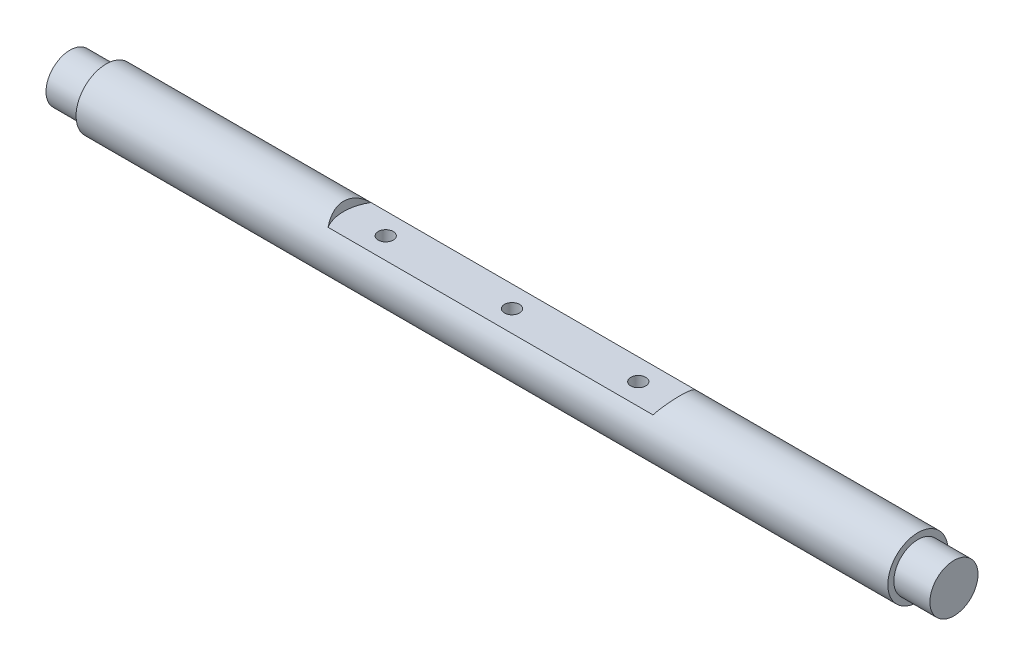
SolidWorks part; units mm, degrees
ref_plane "Plan de face" through (0, 0, 0) normal (0, 0, 1) x (1, 0, 0)
ref_plane "Plan de dessus" through (0, 0, 0) normal (0, 1, 0) x (1, 0, 0)
ref_plane "Plan de droite" through (0, 0, 0) normal (1, 0, 0) x (0, 0, -1)
sketch "Esquisse1" plane through (0, 0, 0) normal (0, 0, 1) x (1, 0, 0)
  line L0 (-67.5, 5) -> (67.5, 5)
  line L1 (67.5, 5) -> (67.5, 4)
  line L2 (67.5, 4) -> (73.5, 4)
  line L3 (73.5, 4) -> (73.5, 0)
  line L4 (73.5, 0) -> (-73.5, 0)
  line L5 (-73.5, 0) -> (-73.5, 4)
  line L6 (-73.5, 4) -> (-67.5, 4)
  line L7 (-67.5, 4) -> (-67.5, 5)
  line L8 (-73.5, 0) -> (-79.5, 0) construction
  dimension "D1" = 6
  dimension "D2" = 135
  dimension "D3" = 147
  dimension "D4" = 8
  dimension "D5" = 10
revolve "Révolution1" add sketch "Esquisse1" angle 360 about L8
sketch "Esquisse2" plane through (0, 0, 0) normal (0, 1, 0) x (1, 0, 0)
  line L0 (-21, 0) -> (21, 0) construction
  circle A0 centre (-21, 0) radius 1.25
  circle A1 centre (21, 0) radius 1.25
  circle A2 centre (0, 0) radius 1.25
  dimension "D1" = 2.5
  dimension "D2" = 42
extrude "Enlèv. mat.-Extru.1" cut sketch "Esquisse2" against normal through all both and the other way through all
sketch "Esquisse3" plane through (0, 0, 0) normal (0, 1, 0) x (1, 0, 0)
  line L0 (-21, 0) -> (21, 0) construction
  line L1 (-21, 7) -> (21, 7)
  line L2 (-21, -7) -> (21, -7)
  arc A0 (-21, 7) -> (-21, -7) centre (-21, 0) ccw
  arc A1 (21, -7) -> (21, 7) centre (21, 0) ccw
  point P2 (0, 0)
  dimension "D1" = 14
  dimension "D2" = 42
extrude "Enlèv. mat.-Extru.2" cut sketch "Esquisse3" along normal blind 10 from offset 3.5
